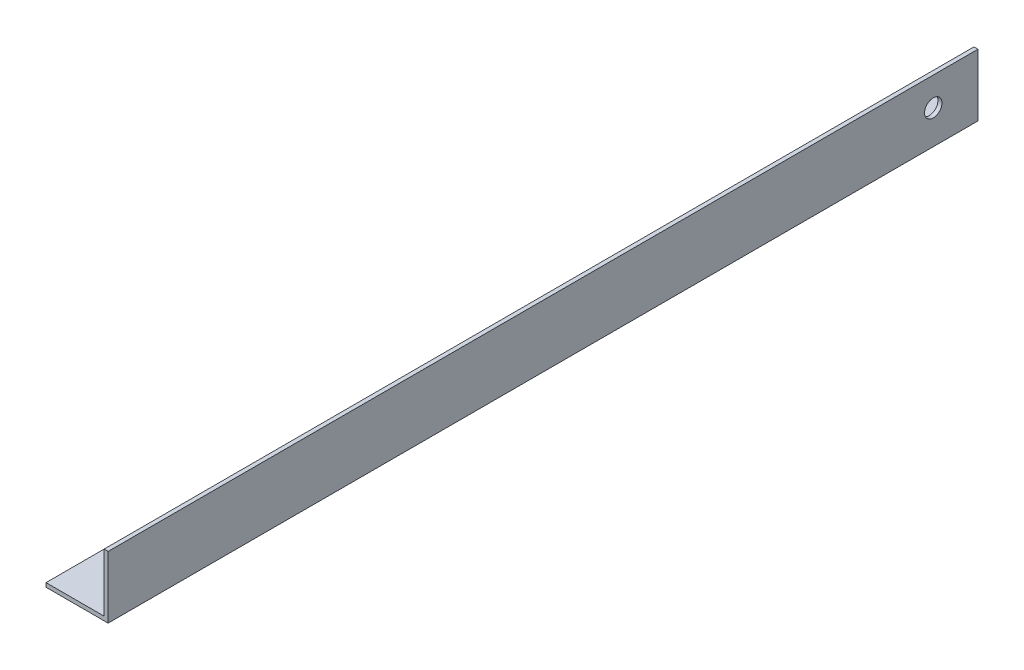
SolidWorks part; units mm, degrees
material "6061 Alloy"
ref_plane "Front Plane" through (0, 0, 0) normal (0, 0, 1) x (1, 0, 0)
ref_plane "Top Plane" through (0, 0, 0) normal (0, 1, 0) x (1, 0, 0)
ref_plane "Right Plane" through (0, 0, 0) normal (1, 0, 0) x (0, 0, -1)
sketch "Sketch1" plane through (0, 0, 0) normal (0, 0, 1) x (1, 0, 0)
  line L1 (-47.7896, 0) -> (-22.3896, 0)
  line L2 (-47.7896, 0) -> (-47.7896, -25.4)
  line L3 (-47.7896, -25.4) -> (-22.3896, -25.4)
  line L4 (-22.3896, 0) -> (-22.3896, -25.4)
  dimension "D1" = 25.4
  dimension "D2" = 25.4
extrude "Boss-Extrude1" add sketch "Sketch1" along normal blind 355.6
sketch "Sketch3" plane through (0, 0, 355.6) normal (0, 0, 1) x (1, 0, 0)
  line L1 (-50.2144, 2.729) -> (-24.0406, 2.729)
  line L2 (-50.2144, 2.729) -> (-50.2144, -23.749)
  line L3 (-50.2144, -23.749) -> (-24.0406, -23.749)
  line L4 (-24.0406, 2.729) -> (-24.0406, -23.749)
  line L5 (-50.2144, 2.729) -> (-24.0406, -23.749) construction
  line L6 (-50.2144, -23.749) -> (-24.0406, 2.729) construction
  line L8 (-22.3896, -25.4) -> (-22.3896, 0) construction
  line L9 (-47.7896, -25.4) -> (-22.3896, -25.4) construction
  point P0 (-37.1275, -10.51)
  dimension "D3" = 1.651
  dimension "D4" = 1.651
extrude "Cut-Extrude2" cut sketch "Sketch3" against normal blind 355.6
sketch "Sketch5" plane through (-22.3896, 0, 0) normal (1, 0, 0) x (0, 0, -1)
  line L2 (-355.6, -25.4) -> (-355.6, 0) construction
  circle A0 centre (-18.288, -11.6485) radius 3.556
  dimension "D1" = 7.112
  dimension "D2" = 337.312
extrude "Cut-Extrude3" cut sketch "Sketch5" against normal through all
